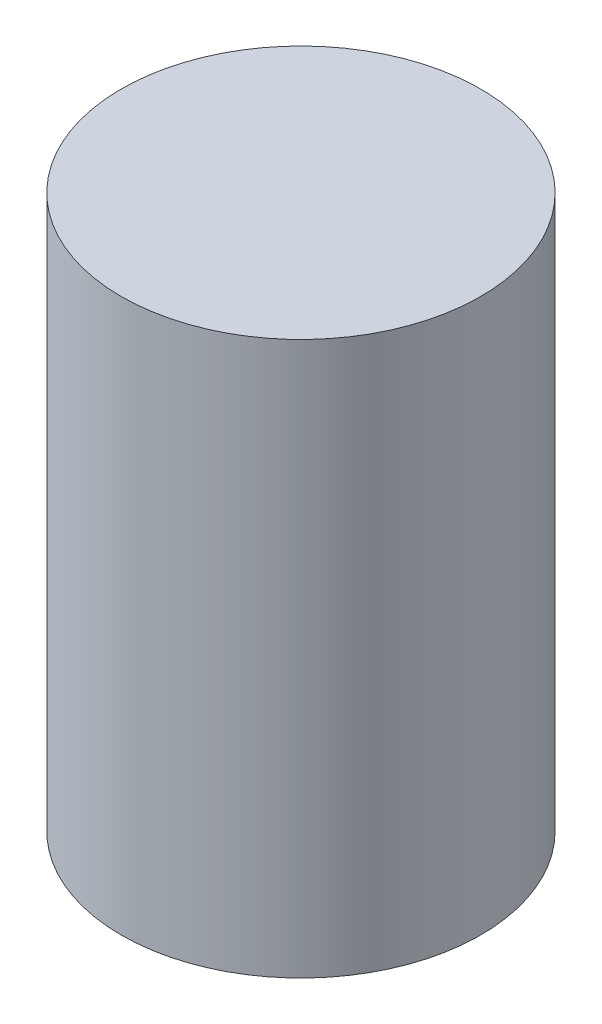
SolidWorks part; units mm, degrees
ref_plane "Front Plane" through (0, 0, 0) normal (0, 0, 1) x (1, 0, 0)
ref_plane "Top Plane" through (0, 0, 0) normal (0, 1, 0) x (1, 0, 0)
ref_plane "Right Plane" through (0, 0, 0) normal (1, 0, 0) x (0, 0, -1)
sketch "Sketch1" plane through (0, 0, 0) normal (0, 1, 0) x (1, 0, 0)
  circle A0 centre (0, 0) radius 3.9
extrude "Boss-Extrude1" add sketch "Sketch1" along normal blind 12
sketch "Sketch3" plane through (0, 0, 0) normal (0, -1, 0) x (1, 0, 0)
  line L0 (-3.8969, -0.1542) -> (3.8969, 0.1542)
  circle A0 centre (0, 0) radius 3.9 construction
  point P6 (0, 0)
